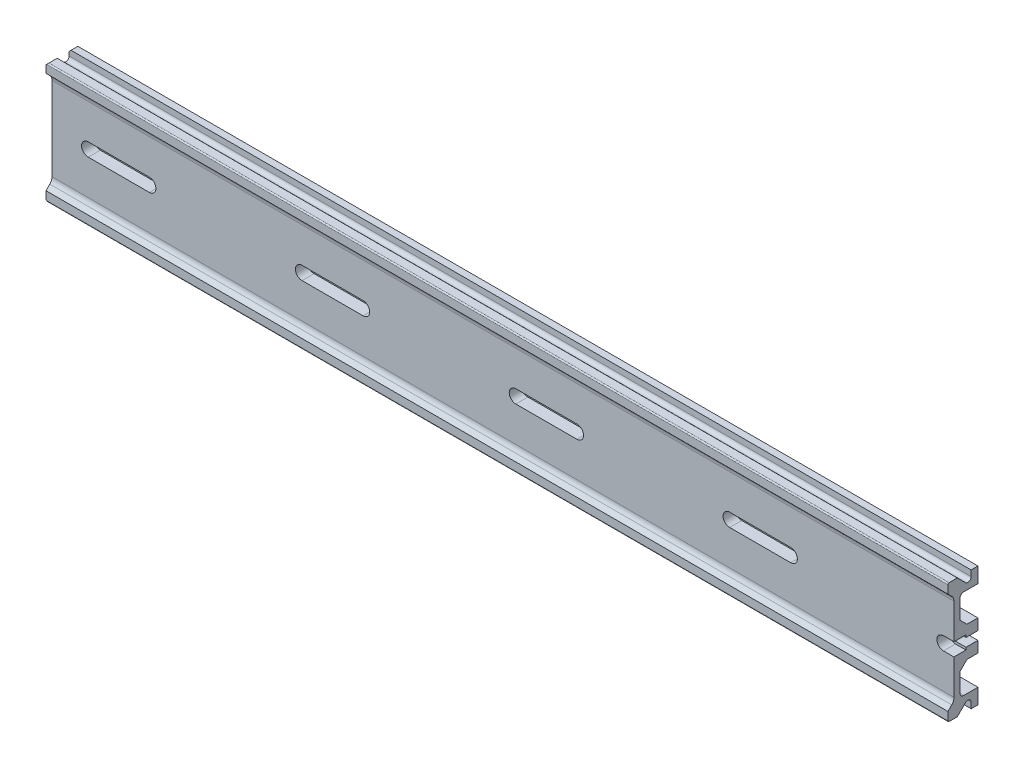
SolidWorks part; units mm, degrees
ref_plane "Front Plane" through (0, 0, 0) normal (0, 0, 1) x (1, 0, 0)
ref_plane "Top Plane" through (0, 0, 0) normal (0, 1, 0) x (1, 0, 0)
ref_plane "Right Plane" through (0, 0, 0) normal (1, 0, 0) x (0, 0, -1)
ref_plane "Plane1" through (0, 0, 0) normal (0, 0, -1) x (-1, 0, 0)
sketch "Sketch1" plane through (0, 0, 0) normal (0, 0, -1) x (-1, 0, 0)
  line L0 (-500, 50) -> (-500, -50)
  line L1 (-500, -50) -> (500, -50)
  line L2 (500, -50) -> (500, 50)
  line L3 (500, 50) -> (-500, 50)
extrude "Boss-Extrude1" add sketch "Sketch1" against normal blind 25
sketch "Sketch2" plane through (500, 0, 0) normal (1, 0, 0) x (0, 0, -1)
  line L0 (0, 37.3) -> (-15, 37.3)
  line L1 (-15, 37.3) -> (-15, 12.7)
  line L2 (-15, 12.7) -> (-0.1, 12.7)
  line L3 (-0.1, 12.7) -> (-0.1, -12.7)
  line L4 (-0.1, -12.7) -> (-15, -12.7)
  line L5 (-15, -12.7) -> (-15, -37.3)
  line L6 (-15, -37.3) -> (0, -37.3)
  line L7 (0, -37.3) -> (0, 37.3)
extrude "Cut-Extrude1" cut sketch "Sketch2" against normal through all
sketch "Sketch3" plane through (500, 0, 0) normal (1, 0, 0) x (0, 0, -1)
  line L0 (-17.2, -50) -> (-5.7, -50)
  line L1 (-5.7, -50) -> (-5.7, -45.1577)
  line L2 (-10.4077, -43.2077) -> (-17.2, -50)
  arc A0 (-5.7, -45.1577) -> (-10.4077, -43.2077) centre (-8.4577, -45.1577) ccw
extrude "Cut-Extrude2" cut sketch "Sketch3" against normal through all
sketch "Sketch4" plane through (500, 0, 0) normal (1, 0, 0) x (0, 0, -1)
  line L0 (-25, -42.2437) -> (-20, -37.2437)
  line L1 (-20, -37.2437) -> (-20, 37.2437)
  line L2 (-20, 37.2437) -> (-25, 42.2437)
  line L3 (-25, 42.2437) -> (-25, -42.2437)
extrude "Cut-Extrude3" cut sketch "Sketch4" against normal through all
sketch "Sketch5" plane through (500, 0, 0) normal (1, 0, 0) x (0, 0, -1)
  line L0 (-5.7, 50) -> (-17.2, 50)
  line L1 (-17.2, 50) -> (-10.4077, 43.2077)
  line L2 (-5.7, 45.1577) -> (-5.7, 50)
  arc A0 (-10.4077, 43.2077) -> (-5.7, 45.1577) centre (-8.4577, 45.1577) ccw
extrude "Cut-Extrude4" cut sketch "Sketch5" against normal through all
sketch "Sketch6" plane through (0, 0, 20) normal (0, 0, 1) x (1, 0, 0)
  line L0 (419.1, -5.5) -> (469.9, -5.5)
  line L1 (469.9, 5.5) -> (419.1, 5.5)
  arc A0 (469.9, -5.5) -> (469.9, 5.5) centre (469.9, 0) ccw
  arc A1 (419.1, 5.5) -> (419.1, -5.5) centre (419.1, 0) ccw
extrude "Cut-Extrude5" cut sketch "Sketch6" against normal blind 10
sketch "Sketch7" plane through (0, 0, 0.1) normal (0, 0, -1) x (-1, 0, 0)
  line L0 (-469.9, -3.5) -> (-419.1, -3.5)
  line L1 (-419.1, 3.5) -> (-469.9, 3.5)
  arc A0 (-419.1, -3.5) -> (-419.1, 3.5) centre (-419.1, 0) ccw
  arc A1 (-469.9, 3.5) -> (-469.9, -3.5) centre (-469.9, 0) ccw
extrude "Cut-Extrude6" cut sketch "Sketch7" against normal through all
sketch "Sketch8" plane through (0, 0, 20) normal (0, 0, 1) x (1, 0, 0)
  line L0 (241.3, -5.5) -> (292.1, -5.5)
  line L1 (292.1, 5.5) -> (241.3, 5.5)
  arc A0 (292.1, -5.5) -> (292.1, 5.5) centre (292.1, 0) ccw
  arc A1 (241.3, 5.5) -> (241.3, -5.5) centre (241.3, 0) ccw
extrude "Cut-Extrude7" cut sketch "Sketch8" against normal blind 10
sketch "Sketch9" plane through (0, 0, 0.1) normal (0, 0, -1) x (-1, 0, 0)
  line L0 (-292.1, -3.5) -> (-241.3, -3.5)
  line L1 (-241.3, 3.5) -> (-292.1, 3.5)
  arc A0 (-292.1, 3.5) -> (-292.1, -3.5) centre (-292.1, 0) ccw
  arc A1 (-241.3, -3.5) -> (-241.3, 3.5) centre (-241.3, 0) ccw
extrude "Cut-Extrude8" cut sketch "Sketch9" against normal through all
sketch "Sketch10" plane through (0, 0, 20) normal (0, 0, 1) x (1, 0, 0)
  line L0 (63.5, -5.5) -> (114.3, -5.5)
  line L1 (114.3, 5.5) -> (63.5, 5.5)
  arc A0 (114.3, -5.5) -> (114.3, 5.5) centre (114.3, 0) ccw
  arc A1 (63.5, 5.5) -> (63.5, -5.5) centre (63.5, 0) ccw
extrude "Cut-Extrude9" cut sketch "Sketch10" against normal blind 10
sketch "Sketch11" plane through (0, 0, 0.1) normal (0, 0, -1) x (-1, 0, 0)
  line L0 (-114.3, -3.5) -> (-63.5, -3.5)
  line L1 (-63.5, 3.5) -> (-114.3, 3.5)
  arc A0 (-114.3, 3.5) -> (-114.3, -3.5) centre (-114.3, 0) ccw
  arc A1 (-63.5, -3.5) -> (-63.5, 3.5) centre (-63.5, 0) ccw
extrude "Cut-Extrude10" cut sketch "Sketch11" against normal through all
sketch "Sketch12" plane through (0, 0, 20) normal (0, 0, 1) x (1, 0, 0)
  line L0 (-114.3, -5.5) -> (-63.5, -5.5)
  line L1 (-63.5, 5.5) -> (-114.3, 5.5)
  arc A0 (-63.5, -5.5) -> (-63.5, 5.5) centre (-63.5, 0) ccw
  arc A1 (-114.3, 5.5) -> (-114.3, -5.5) centre (-114.3, 0) ccw
extrude "Cut-Extrude11" cut sketch "Sketch12" against normal blind 10
sketch "Sketch13" plane through (0, 0, 0.1) normal (0, 0, -1) x (-1, 0, 0)
  line L0 (63.5, -3.5) -> (114.3, -3.5)
  line L1 (114.3, 3.5) -> (63.5, 3.5)
  arc A0 (63.5, 3.5) -> (63.5, -3.5) centre (63.5, 0) ccw
  arc A1 (114.3, -3.5) -> (114.3, 3.5) centre (114.3, 0) ccw
extrude "Cut-Extrude12" cut sketch "Sketch13" against normal through all
sketch "Sketch14" plane through (0, 0, 20) normal (0, 0, 1) x (1, 0, 0)
  line L0 (-292.1, -5.5) -> (-241.3, -5.5)
  line L1 (-241.3, 5.5) -> (-292.1, 5.5)
  arc A0 (-241.3, -5.5) -> (-241.3, 5.5) centre (-241.3, 0) ccw
  arc A1 (-292.1, 5.5) -> (-292.1, -5.5) centre (-292.1, 0) ccw
extrude "Cut-Extrude13" cut sketch "Sketch14" against normal blind 10
sketch "Sketch15" plane through (0, 0, 0.1) normal (0, 0, -1) x (-1, 0, 0)
  line L0 (241.3, -3.5) -> (292.1, -3.5)
  line L1 (292.1, 3.5) -> (241.3, 3.5)
  arc A0 (241.3, 3.5) -> (241.3, -3.5) centre (241.3, 0) ccw
  arc A1 (292.1, -3.5) -> (292.1, 3.5) centre (292.1, 0) ccw
extrude "Cut-Extrude14" cut sketch "Sketch15" against normal through all
sketch "Sketch16" plane through (0, 0, 20) normal (0, 0, 1) x (1, 0, 0)
  line L0 (-469.9, -5.5) -> (-419.1, -5.5)
  line L1 (-419.1, 5.5) -> (-469.9, 5.5)
  arc A0 (-419.1, -5.5) -> (-419.1, 5.5) centre (-419.1, 0) ccw
  arc A1 (-469.9, 5.5) -> (-469.9, -5.5) centre (-469.9, 0) ccw
extrude "Cut-Extrude15" cut sketch "Sketch16" against normal blind 10
sketch "Sketch17" plane through (0, 0, 0.1) normal (0, 0, -1) x (-1, 0, 0)
  line L0 (419.1, -3.5) -> (469.9, -3.5)
  line L1 (469.9, 3.5) -> (419.1, 3.5)
  arc A0 (419.1, 3.5) -> (419.1, -3.5) centre (419.1, 0) ccw
  arc A1 (469.9, -3.5) -> (469.9, 3.5) centre (469.9, 0) ccw
extrude "Cut-Extrude16" cut sketch "Sketch17" against normal through all
chamfer "Chamfer1" distance 5.8 angle 45 2 edges at (0, -12.7, 15) (0, 12.7, 15)
chamfer "Chamfer2" distance 1.5 angle 45 8 edges at (-500, 50, 21.1) (-500, -50, 21.1) (500, -50, 2.85) (500, 50, 2.85) (-500, -50, 2.85) (500, -50, 21.1) (500, 50, 21.1) (-500, 50, 2.85)
fillet "Fillet1" radius 1 2 edges at (0, -50, 25) (0, 50, 25)
fillet "Fillet2" radius 3.2 2 edges at (0, -37.3, 15) (0, 37.3, 15)
fillet "Fillet3" radius 6.3 2 edges at (0, -37.2437, 20) (0, 37.2437, 20)
sketch "Sketch18" plane through (500, 0, 0) normal (1, 0, 0) x (0, 0, -1)
  line L0 (-5.7, 50) -> (-5.7, 48.5) construction
  line L1 (0, 48.5) -> (0, 50) construction
  line L2 (0, 50) -> (-5.7, 50) construction
  line L3 (-17.2, 50) -> (-24, 50) construction
  line L4 (-25, 49) -> (-25, 48.5) construction
  line L5 (-15.7, 48.5) -> (-17.2, 50) construction
  line L6 (-5.7, -48.5) -> (-5.7, -50) construction
  line L7 (-5.7, -50) -> (0, -50) construction
  line L8 (0, -50) -> (0, -48.5) construction
  line L9 (-25, -48.5) -> (-25, -49) construction
  line L10 (-24, -50) -> (-17.2, -50) construction
  line L11 (-17.2, -50) -> (-15.7, -48.5) construction
  line L12 (-5.7, -45.1577) -> (-5.7, -48.5) construction
  line L13 (0, -48.5) -> (0, -37.3) construction
  line L14 (0, -37.3) -> (-11.8, -37.3) construction
  line L15 (-15, -34.1) -> (-15, -18.5) construction
  line L16 (-15, -18.5) -> (-9.2, -12.7) construction
  line L17 (-9.2, -12.7) -> (-0.1, -12.7) construction
  line L18 (-0.1, -12.7) -> (-0.1, 12.7) construction
  line L19 (-0.1, 12.7) -> (-9.2, 12.7) construction
  line L20 (-9.2, 12.7) -> (-15, 18.5) construction
  line L21 (-15, 18.5) -> (-15, 34.1) construction
  line L22 (-11.8, 37.3) -> (0, 37.3) construction
  line L23 (0, 37.3) -> (0, 48.5) construction
  line L24 (-5.7, 48.5) -> (-5.7, 45.1577) construction
  line L25 (-10.4077, 43.2077) -> (-15.7, 48.5) construction
  line L26 (-25, 48.5) -> (-25, 42.2437) construction
  line L27 (-25, 42.2437) -> (-21.8452, 39.0889) construction
  line L28 (-20, 34.6341) -> (-20, -34.6341) construction
  line L29 (-21.8452, -39.0889) -> (-25, -42.2437) construction
  line L30 (-25, -42.2437) -> (-25, -48.5) construction
  line L31 (-15.7, -48.5) -> (-10.4077, -43.2077) construction
  line L32 (-5.7, 50) -> (-5.7, 48.5)
  line L33 (0, 48.5) -> (0, 50)
  line L34 (0, 50) -> (-5.7, 50)
  line L35 (-17.2, 50) -> (-24, 50)
  line L36 (-25, 49) -> (-25, 48.5)
  line L37 (-15.7, 48.5) -> (-17.2, 50)
  line L38 (-5.7, -48.5) -> (-5.7, -50)
  line L39 (-5.7, -50) -> (0, -50)
  line L40 (0, -50) -> (0, -48.5)
  line L41 (-25, -48.5) -> (-25, -49)
  line L42 (-24, -50) -> (-17.2, -50)
  line L43 (-17.2, -50) -> (-15.7, -48.5)
  line L44 (-5.7, -45.1577) -> (-5.7, -48.5)
  line L45 (0, -48.5) -> (0, -37.3)
  line L46 (0, -37.3) -> (-11.8, -37.3)
  line L47 (-15, -34.1) -> (-15, -18.5)
  line L48 (-15, -18.5) -> (-9.2, -12.7)
  line L49 (-9.2, -12.7) -> (-0.1, -12.7)
  line L50 (-0.1, -12.7) -> (-0.1, 12.7)
  line L51 (-0.1, 12.7) -> (-9.2, 12.7)
  line L52 (-9.2, 12.7) -> (-15, 18.5)
  line L53 (-15, 18.5) -> (-15, 34.1)
  line L54 (-11.8, 37.3) -> (0, 37.3)
  line L55 (0, 37.3) -> (0, 48.5)
  line L56 (-5.7, 48.5) -> (-5.7, 45.1577)
  line L57 (-10.4077, 43.2077) -> (-15.7, 48.5)
  line L58 (-25, 48.5) -> (-25, 42.2437)
  line L59 (-25, 42.2437) -> (-21.8452, 39.0889)
  line L60 (-20, 34.6341) -> (-20, -34.6341)
  line L61 (-21.8452, -39.0889) -> (-25, -42.2437)
  line L62 (-25, -42.2437) -> (-25, -48.5)
  line L63 (-15.7, -48.5) -> (-10.4077, -43.2077)
  arc A0 (-24, 50) -> (-25, 49) centre (-24, 49) ccw construction
  arc A1 (-25, -49) -> (-24, -50) centre (-24, -49) ccw construction
  arc A2 (-15, -34.1) -> (-11.8, -37.3) centre (-11.8, -34.1) ccw construction
  arc A3 (-11.8, 37.3) -> (-15, 34.1) centre (-11.8, 34.1) ccw construction
  arc A4 (-10.4077, 43.2077) -> (-5.7, 45.1577) centre (-8.4577, 45.1577) ccw construction
  arc A5 (-20, 34.6341) -> (-21.8452, 39.0889) centre (-26.3, 34.6341) ccw construction
  arc A6 (-21.8452, -39.0889) -> (-20, -34.6341) centre (-26.3, -34.6341) ccw construction
  arc A7 (-5.7, -45.1577) -> (-10.4077, -43.2077) centre (-8.4577, -45.1577) ccw construction
  arc A8 (-24, 50) -> (-25, 49) centre (-24, 49) ccw
  arc A9 (-25, -49) -> (-24, -50) centre (-24, -49) ccw
  arc A10 (-15, -34.1) -> (-11.8, -37.3) centre (-11.8, -34.1) ccw
  arc A11 (-11.8, 37.3) -> (-15, 34.1) centre (-11.8, 34.1) ccw
  arc A12 (-10.4077, 43.2077) -> (-5.7, 45.1577) centre (-8.4577, 45.1577) ccw
  arc A13 (-20, 34.6341) -> (-21.8452, 39.0889) centre (-26.3, 34.6341) ccw
  arc A14 (-21.8452, -39.0889) -> (-20, -34.6341) centre (-26.3, -34.6341) ccw
  arc A15 (-5.7, -45.1577) -> (-10.4077, -43.2077) centre (-8.4577, -45.1577) ccw
extrude "Cut-Extrude17" cut sketch "Sketch18" against normal blind 250
